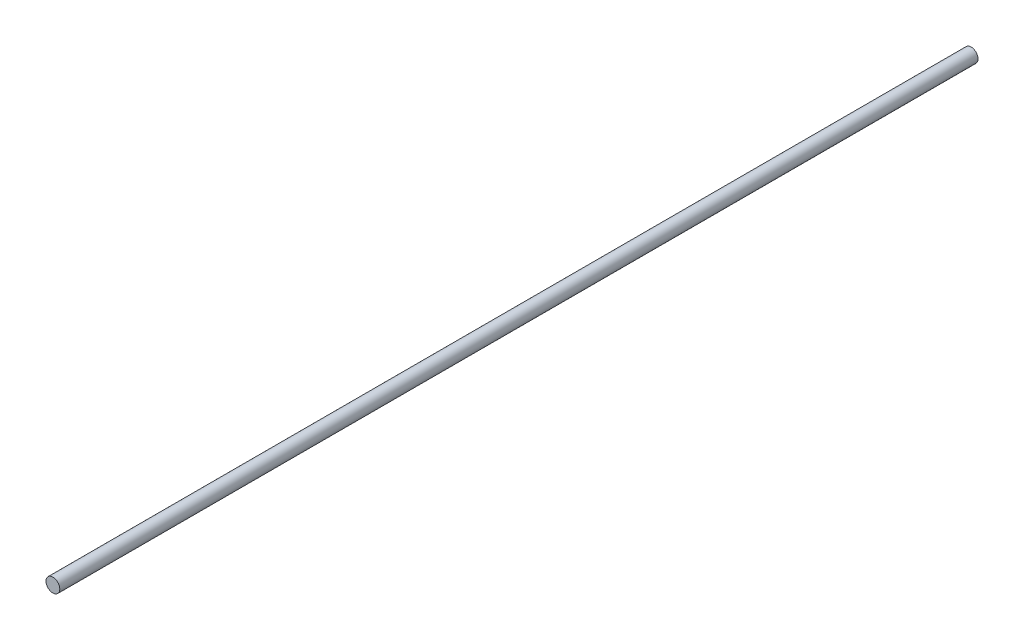
SolidWorks part; units mm, degrees
ref_plane "Front Plane" through (0, 0, 0) normal (0, 0, 1) x (1, 0, 0)
ref_plane "Top Plane" through (0, 0, 0) normal (0, 1, 0) x (1, 0, 0)
ref_plane "Right Plane" through (0, 0, 0) normal (1, 0, 0) x (0, 0, -1)
sketch "Sketch1" plane through (0, 0, 0) normal (0, 0, 1) x (1, 0, 0)
  circle A0 centre (0, 0) radius 4.7625
  dimension "D1" = 9.525
extrude "Boss-Extrude1" add sketch "Sketch1" along normal blind 635
